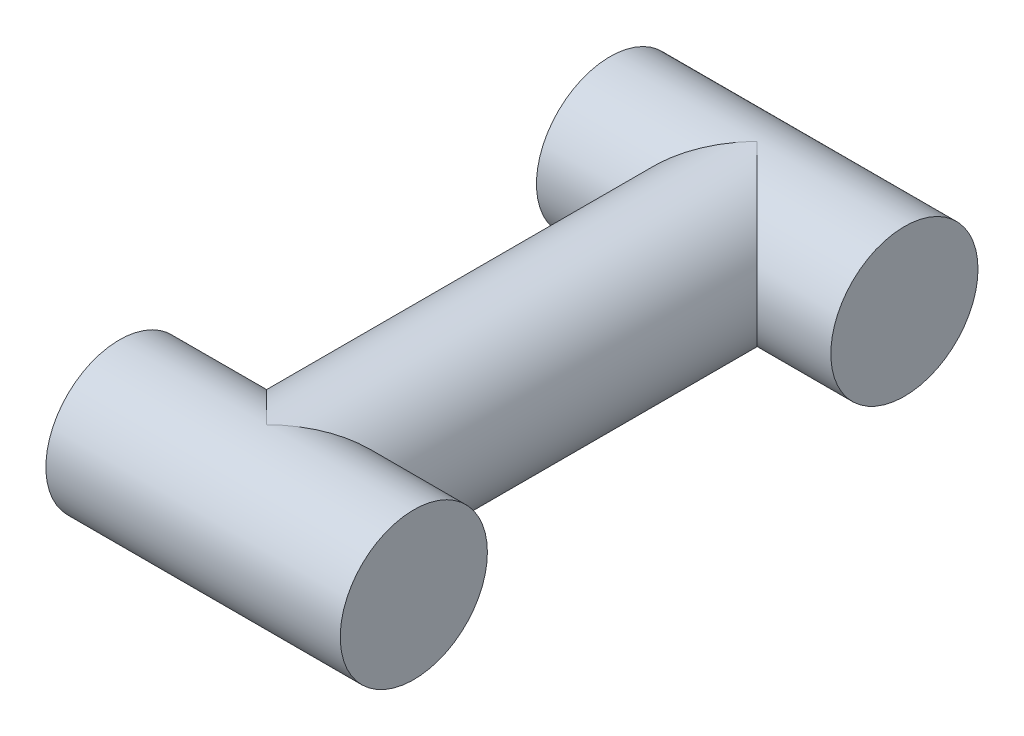
SolidWorks part; units mm, degrees
ref_plane "up基准面" through (0, 0, 0) normal (0, 0, 1) x (1, 0, 0)
ref_plane "前基准面" through (0, 0, 0) normal (0, 1, 0) x (1, 0, 0)
ref_plane "右视基准面" through (0, 0, 0) normal (1, 0, 0) x (0, 0, -1)
sketch "草图7" plane through (0, 0, 0) normal (1, 0, 0) x (0, 0, -1)
  circle A0 centre (0, 0) radius 15
extrude "凸台-拉伸5" add sketch "草图7" along normal mid plane 60
sketch "草图8" plane through (0, 0, 0) normal (0, 0, 1) x (1, 0, 0)
  circle A0 centre (0, 0) radius 15
extrude "凸台-拉伸6" add sketch "草图8" along normal blind 100
sketch "草图9" plane through (0, 0, 0) normal (1, 0, 0) x (0, 0, -1)
  line L0 (-100, 15) -> (-100, -15) construction
  circle A0 centre (-100, 0) radius 15
extrude "凸台-拉伸7" add sketch "草图9" along normal mid plane 60
